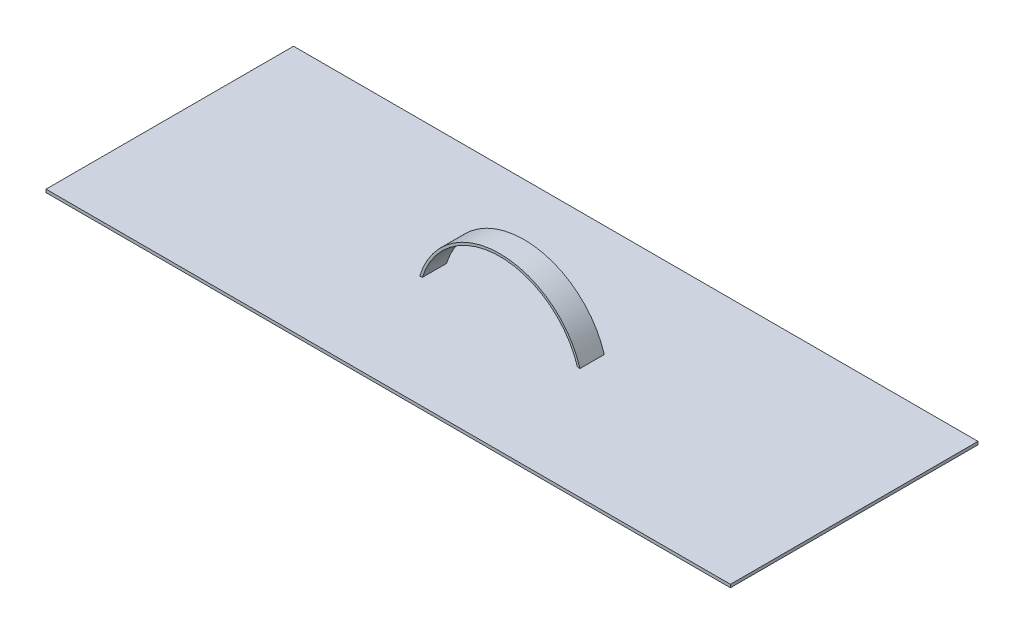
SolidWorks part; units mm, degrees
ref_plane "Front Plane" through (0, 0, 0) normal (0, 0, 1) x (1, 0, 0)
ref_plane "Top Plane" through (0, 0, 0) normal (0, 1, 0) x (1, 0, 0)
ref_plane "Right Plane" through (0, 0, 0) normal (1, 0, 0) x (0, 0, -1)
sketch "Sketch1" plane through (0, 2.5, 0) normal (0, 1, 0) x (1, 0, 0)
  line L4 (-11, 11) -> (-11, -71)
  line L5 (-11, -71) -> (251, -71)
  line L6 (251, -71) -> (251, 11)
  line L7 (251, 11) -> (-11, 11)
  line L8 (-11, 11) -> (-11, -71)
  line L9 (-11, -71) -> (251, -71)
  line L10 (251, -71) -> (251, 11)
  line L11 (251, 11) -> (-11, 11)
  dimension "D1" = 0
extrude "Boss-Extrude1" add sketch "Sketch1" along normal blind 10
sketch "Sketch2" plane through (0, 12.5, 0) normal (0, 1, 0) x (1, 0, 0)
  line L1 (-11, -71) -> (-21, -71) construction
  line L2 (-11, -71) -> (-11, -81) construction
  line L3 (-11, -81) -> (-21, -81) construction
  line L4 (-21, -71) -> (-21, -81) construction
  line L5 (251, 11) -> (261, 11) construction
  line L6 (251, 11) -> (251, 21) construction
  line L7 (251, 21) -> (261, 21) construction
  line L8 (261, 11) -> (261, 21) construction
  line L9 (-21, -81) -> (261, -81)
  line L10 (-21, -81) -> (-21, 21)
  line L11 (-21, 21) -> (261, 21)
  line L12 (261, -81) -> (261, 21)
  dimension "D1" = 10
extrude "Boss-Extrude2" add sketch "Sketch2" along normal blind 1.25
ref_plane "Plane1" through (0, 0, 30) normal (0, 0, 1) x (1, 0, 0)
sketch "Sketch3" plane through (0, 0, 30) normal (0, 0, 1) x (1, 0, 0)
  line L0 (86.5, 3.75) -> (85.5, 3.75) construction
  line L1 (-21, 13.75) -> (261, 13.75) construction
  line L2 (120, 3.75) -> (120, 13.75) construction
  circle A0 centre (120, 3.75) radius 34.5
  circle A1 centre (120, 3.75) radius 33.5
  point P6 (0, 0)
  dimension "D1" = 1
  dimension "D2" = 69
  dimension "D3" = 10
extrude "Boss-Extrude3" add sketch "Sketch3" along normal mid plane 10
